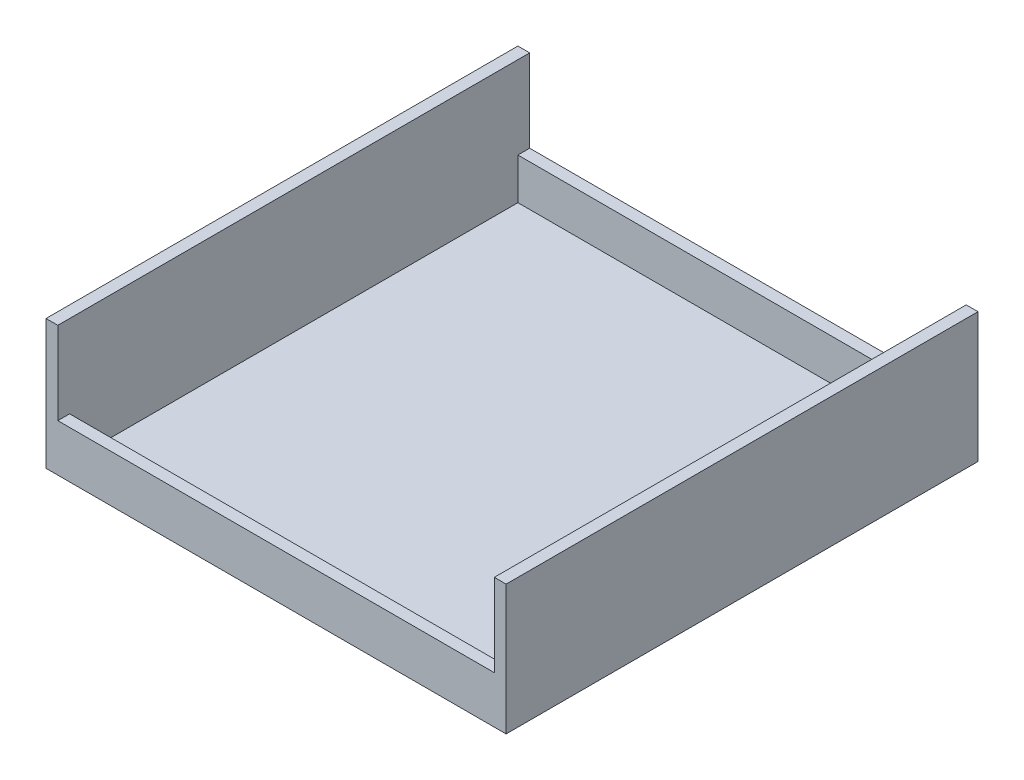
SolidWorks part; units mm, degrees
ref_plane "Front Plane" through (0, 0, 0) normal (0, 0, 1) x (1, 0, 0)
ref_plane "Top Plane" through (0, 0, 0) normal (0, 1, 0) x (1, 0, 0)
ref_plane "Right Plane" through (0, 0, 0) normal (1, 0, 0) x (0, 0, -1)
sketch "Sketch2" plane through (0, 0, 0) normal (0, 1, 0) x (1, 0, 0)
  line L1 (0, 0) -> (78, 0)
  line L2 (0, 0) -> (0, 80)
  line L3 (0, 80) -> (78, 80)
  line L4 (78, 0) -> (78, 80)
  dimension "D1" = 78
  dimension "D2" = 80
extrude "Boss-Extrude1" add sketch "Sketch2" along normal blind 1
sketch "Sketch3" plane through (0, 1, 0) normal (0, 1, 0) x (1, 0, 0)
  line L0 (78, 80) -> (0, 80) construction
  line L1 (0, 0) -> (2, 0)
  line L2 (0, 0) -> (0, 80)
  line L3 (0, 80) -> (2, 80)
  line L4 (2, 0) -> (2, 80)
  line L6 (78, 0) -> (76, 0)
  line L7 (78, 0) -> (78, 80)
  line L8 (78, 80) -> (76, 80)
  line L9 (76, 0) -> (76, 80)
  dimension "D1" = 2
extrude "Boss-Extrude2" add sketch "Sketch3" along normal blind 21
sketch "Sketch4" plane through (0, 1, 0) normal (0, 1, 0) x (1, 0, 0)
  line L0 (76, 80) -> (76, 0) construction
  line L1 (2, 0) -> (76, 0)
  line L2 (2, 0) -> (2, 2)
  line L3 (2, 2) -> (76, 2)
  line L4 (76, 0) -> (76, 2)
  line L5 (2, 0) -> (2, 80) construction
  line L6 (76, 80) -> (2, 80)
  line L7 (76, 80) -> (76, 78)
  line L8 (76, 78) -> (2, 78)
  line L9 (2, 80) -> (2, 78)
  dimension "D1" = 2
extrude "Boss-Extrude3" add sketch "Sketch4" along normal blind 7
